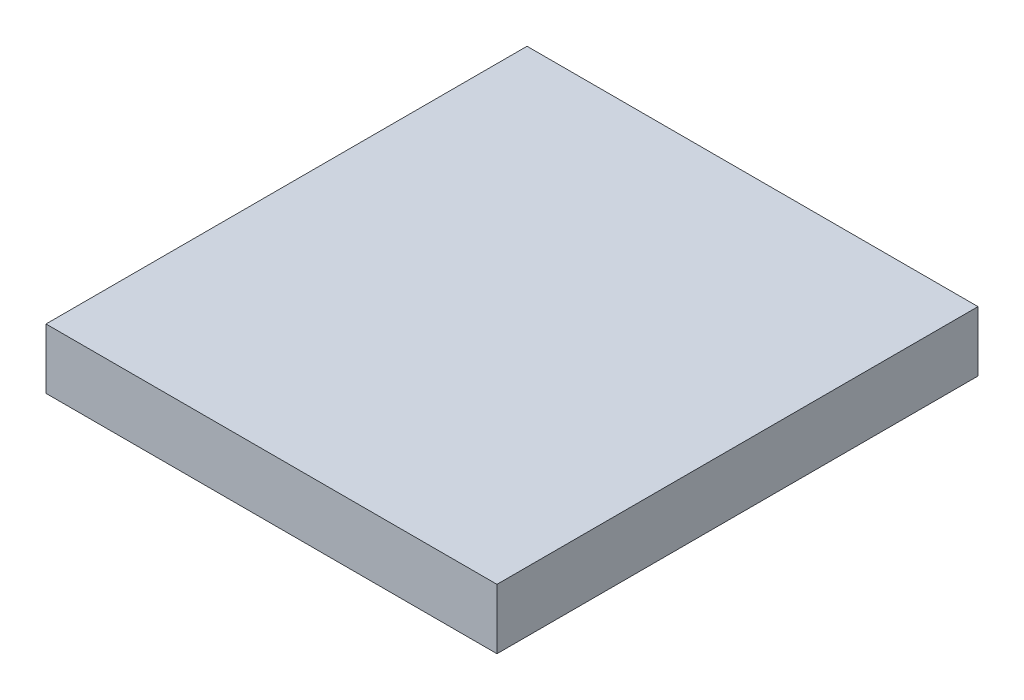
SolidWorks part; units mm, degrees
ref_plane "Front Plane" through (0, 0, 0) normal (0, 0, 1) x (1, 0, 0)
ref_plane "Top Plane" through (0, 0, 0) normal (0, 1, 0) x (1, 0, 0)
ref_plane "Right Plane" through (0, 0, 0) normal (1, 0, 0) x (0, 0, -1)
sketch "Sketch1" plane through (0, 0, 0) normal (0, 1, 0) x (1, 0, 0)
  line L0 (-74.7839, 129.2003) -> (-74.7839, -30.7997)
  line L1 (-74.7839, -30.7997) -> (75.2161, -30.7997)
  line L2 (75.2161, -30.7997) -> (75.2161, 129.2003)
  line L3 (75.2161, 129.2003) -> (-74.7839, 129.2003)
  dimension "D1" = 150
  dimension "D2" = 160
extrude "Boss-Extrude1" add sketch "Sketch1" along normal blind 20
sketch "Sketch2" plane through (0, 0, 0) normal (0, 1, 0) x (1, 0, 0)
  line L0 (-59.7839, 96.7003) -> (-59.7839, 29.2003)
  line L1 (-59.7839, 29.2003) -> (0.2161, 29.2003)
  line L2 (0.2161, 29.2003) -> (0.2161, 96.7003)
  line L3 (0.2161, 96.7003) -> (-59.7839, 96.7003)
  line L5 (-74.7839, -30.7997) -> (75.2161, -30.7997) construction
  line L7 (-74.7839, 129.2003) -> (-74.7839, -30.7997) construction
  line L8 (75.2161, 129.2003) -> (-74.7839, 129.2003) construction
  dimension "D1" = 67.5
  dimension "D2" = 60
  dimension "D3" = 15
  dimension "D4" = 60
  dimension "D5" = 32.5
extrude "Cut-Extrude1" cut sketch "Sketch2" against normal blind 15 and the other way blind 15
sketch "Sketch3" plane through (0, 0, 0) normal (0, 1, 0) x (1, 0, 0)
  line L0 (0.2161, 96.7003) -> (40.2161, 95.4503)
  line L1 (40.2161, 95.4503) -> (40.2161, 89.2003)
  line L2 (40.2161, 89.2003) -> (0.2161, 89.2003)
  line L3 (0.2161, 96.7003) -> (0.2161, 29.2003) construction
  line L4 (0.2161, 89.2003) -> (97.7865, 89.2003) construction
  line L5 (0.2161, 96.7003) -> (0.2161, 89.2003)
  dimension "D1" = 40
  dimension "D2" = 6.25
  dimension "D3" = 7.5
revolve "Cut-Revolve1" cut sketch "Sketch3" angle 360 about L4
sketch "Sketch4" plane through (0, 0, 0) normal (0, 1, 0) x (1, 0, 0)
  line L0 (0.2161, 79.2003) -> (60.2161, 77.9503)
  line L1 (0.2161, 81.7003) -> (0.2161, 29.2003) construction
  line L2 (60.2161, 77.9503) -> (60.2161, 71.7003)
  line L3 (60.2161, 71.7003) -> (0.2161, 71.7003)
  line L4 (0.2161, 71.7003) -> (0.2161, 79.2003)
  line L5 (94.9874, 71.7003) -> (-11.8608, 71.7003) construction
  dimension "D1" = 2.5
  dimension "D2" = 7.5
  dimension "D3" = 6.25
  dimension "D4" = 60
revolve "Cut-Revolve2" cut sketch "Sketch4" angle 360 about L5
sketch "Sketch6" plane through (0, 0, 0) normal (0, 1, 0) x (1, 0, 0)
  line L0 (0.2161, 61.7003) -> (60.2161, 60.4503)
  line L1 (0.2161, 64.2003) -> (0.2161, 29.2003) construction
  line L2 (60.2161, 60.4503) -> (60.2161, 54.2003)
  line L3 (60.2161, 54.2003) -> (0.2161, 54.2003)
  line L4 (0.2161, 54.2003) -> (0.2161, 61.7003)
  line L5 (60.2161, 54.2003) -> (0.2161, 54.2003) construction
  dimension "D1" = 60
  dimension "D2" = 6.25
  dimension "D3" = 7.5
  dimension "D4" = 2.5
revolve "Cut-Revolve3" cut sketch "Sketch6" angle 360 about L5
sketch "Sketch7" plane through (0, 0, 0) normal (0, 1, 0) x (1, 0, 0)
  line L0 (0.2161, 44.2003) -> (60.2161, 42.9503)
  line L1 (0.2161, 46.7003) -> (0.2161, 29.2003) construction
  line L2 (60.2161, 42.9503) -> (60.2161, 36.7003)
  line L3 (60.2161, 36.7003) -> (0.2161, 36.7003)
  line L4 (0.2161, 36.7003) -> (0.2161, 44.2003)
  line L5 (60.2161, 36.7003) -> (0.2161, 36.7003) construction
  dimension "D1" = 60
  dimension "D2" = 7.5
  dimension "D3" = 6.25
  dimension "D4" = 2.5
revolve "Cut-Revolve4" cut sketch "Sketch7" angle 360 about L5
sketch "Sketch11" plane through (0, 0, 0) normal (0, 1, 0) x (1, 0, 0)
  line L0 (-46.1439, 29.2003) -> (28.7625, 1.1104)
  line L1 (0.2161, 29.2003) -> (-59.7839, 29.2003) construction
  line L2 (28.7625, 1.1104) -> (31.3959, 8.1329)
  line L3 (31.3959, 8.1329) -> (-24.7839, 29.2003)
  line L4 (-24.7839, 29.2003) -> (-46.1439, 29.2003)
  line L5 (28.7625, 1.1104) -> (-46.1439, 29.2003) construction
  dimension "D1" = 7.5
  dimension "D2" = 80
  dimension "D3" = 13.64
  dimension "D4" = 25
  dimension "D5" = 60
revolve "Cut-Revolve5" cut sketch "Sketch11" angle 360 about L5
sketch "Sketch13" plane through (0, 0, 0) normal (0, 1, 0) x (1, 0, 0)
  line L0 (-30.0507, 15.1554) -> (-24.7839, 29.2003)
  line L1 (-24.7839, 29.2003) -> (-46.1439, 29.2003)
  line L2 (-46.1439, 29.2003) -> (-30.0507, 15.1554)
extrude "Cut-Extrude6" cut sketch "Sketch13" against normal blind 0.1 and the other way blind 10
sketch "Sketch15" plane through (0, 0, 0) normal (0, 1, 0) x (1, 0, 0)
  line L0 (60.2161, 36.7003) -> (-4.031, 36.7003) construction
  line L1 (60.2161, 30.4503) -> (60.2161, 42.9503) construction
  line L2 (50.2161, 30.242) -> (37.7161, 29.9815)
  line L3 (0.2161, 29.2003) -> (60.2161, 30.4503) construction
  line L6 (50.2161, 31.742) -> (50.2161, 30.242)
  line L7 (50.2161, 31.742) -> (37.7161, 31.4815)
  line L8 (37.7161, 31.4815) -> (37.7161, 29.9815)
  dimension "D1" = 10
  dimension "D2" = 12.5
  dimension "D3" = 1.5
revolve "Revolve2" add sketch "Sketch15" angle 180 about L0
sketch "Sketch16" plane through (0, 0, 0) normal (0, 1, 0) x (1, 0, 0)
  line L0 (60.2161, 36.7003) -> (-8.6318, 36.7003) construction
  line L1 (60.2161, 30.4503) -> (60.2161, 42.9503) construction
  line L2 (25.2161, 29.7211) -> (12.7161, 29.4607)
  line L3 (0.2161, 29.2003) -> (37.7161, 29.9815) construction
  line L6 (25.2161, 31.2211) -> (25.2161, 29.7211)
  line L8 (25.2161, 31.2211) -> (12.7161, 30.9607)
  line L9 (12.7161, 30.9607) -> (12.7161, 29.4607)
  line L10 (37.7161, 31.4815) -> (37.7161, 29.9815) construction
  dimension "D1" = 12.5
  dimension "D2" = 12.5
  dimension "D3" = 1.5
revolve "Revolve3" add sketch "Sketch16" angle 180 about L0
sketch "Sketch17" plane through (0, 0, 0) normal (0, 1, 0) x (1, 0, 0)
  line L0 (60.2161, 54.2003) -> (-2.2399, 54.2003) construction
  line L1 (60.2161, 47.9503) -> (60.2161, 60.4503) construction
  line L2 (50.2161, 47.742) -> (50.2161, 49.242)
  line L3 (0.2161, 46.7003) -> (60.2161, 47.9503) construction
  line L5 (37.7161, 48.9815) -> (37.7161, 47.4815)
  line L6 (37.7161, 47.4815) -> (50.2161, 47.742)
  line L7 (50.2161, 49.242) -> (37.7161, 48.9815)
  dimension "D1" = 1.5
  dimension "D2" = 1.5
  dimension "D3" = 12.5
  dimension "D4" = 10
revolve "Revolve4" add sketch "Sketch17" angle 180 about L0
sketch "Sketch18" plane through (0, 0, 0) normal (0, 1, 0) x (1, 0, 0)
  line L0 (60.2161, 54.2003) -> (-2.3771, 54.2003) construction
  line L1 (60.2161, 47.9503) -> (60.2161, 60.4503) construction
  line L2 (25.2161, 47.2211) -> (25.2161, 48.7211)
  line L3 (0.2161, 46.7003) -> (37.7161, 47.4815) construction
  line L4 (25.2161, 47.2211) -> (12.7161, 46.9607)
  line L5 (12.7161, 46.9607) -> (12.7161, 48.4607)
  line L6 (12.7161, 48.4607) -> (25.2161, 48.7211)
  line L7 (37.7161, 48.9815) -> (37.7161, 47.4815) construction
  dimension "D1" = 1.5
  dimension "D2" = 1.5
  dimension "D3" = 12.5
  dimension "D4" = 12.5
revolve "Revolve5" add sketch "Sketch18" angle 180 about L0
sketch "Sketch19" plane through (0, 0, 0) normal (0, 1, 0) x (1, 0, 0)
  line L0 (60.2161, 71.7003) -> (-2.6664, 71.7003) construction
  line L1 (60.2161, 65.4503) -> (60.2161, 77.9503) construction
  line L2 (50.2161, 65.242) -> (50.2161, 66.742)
  line L3 (0.2161, 64.2003) -> (60.2161, 65.4503) construction
  line L4 (50.2161, 65.242) -> (37.7161, 64.9815)
  line L5 (37.7161, 64.9815) -> (37.7161, 66.4815)
  line L6 (37.7161, 66.4815) -> (50.2161, 66.742)
  dimension "D1" = 10
  dimension "D2" = 12.5
  dimension "D3" = 1.5
  dimension "D4" = 1.5
revolve "Revolve6" add sketch "Sketch19" angle 180 about L0
sketch "Sketch20" plane through (0, 0, 0) normal (0, 1, 0) x (1, 0, 0)
  line L0 (60.2161, 71.7003) -> (-5.3603, 71.7003) construction
  line L1 (60.2161, 65.4503) -> (60.2161, 77.9503) construction
  line L2 (25.2161, 66.2211) -> (25.2161, 64.7211)
  line L3 (0.2161, 64.2003) -> (37.7161, 64.9815) construction
  line L4 (25.2161, 64.7211) -> (12.7161, 64.4607)
  line L5 (12.7161, 64.4607) -> (12.7161, 65.9607)
  line L6 (12.7161, 65.9607) -> (25.2161, 66.2211)
  line L7 (37.7161, 66.4815) -> (37.7161, 64.9815) construction
  dimension "D1" = 12.5
  dimension "D2" = 1.5
  dimension "D3" = 12.5
  dimension "D4" = 1.5
revolve "Revolve7" add sketch "Sketch20" angle 180 about L0
sketch "Sketch21" plane through (0, 0, 0) normal (0, 1, 0) x (1, 0, 0)
  line L0 (40.2161, 89.2003) -> (-5.481, 89.2003) construction
  line L1 (40.2161, 95.4503) -> (40.2161, 82.9503) construction
  line L2 (32.7161, 82.7159) -> (32.7161, 84.2159)
  line L3 (40.2161, 82.9503) -> (0.2161, 81.7003) construction
  line L4 (32.7161, 84.2159) -> (23.3411, 83.9229)
  line L5 (23.3411, 83.9229) -> (23.3411, 82.4229)
  line L6 (23.3411, 82.4229) -> (32.7161, 82.7159)
  dimension "D1" = 1.5
  dimension "D2" = 9.375
  dimension "D3" = 7.5
revolve "Revolve8" add sketch "Sketch21" angle 180 about L0
sketch "Sketch22" plane through (0, 0, 0) normal (0, 1, 0) x (1, 0, 0)
  line L0 (40.2161, 89.2003) -> (-5.8524, 89.2003) construction
  line L1 (40.2161, 95.4503) -> (40.2161, 82.9503) construction
  line L2 (13.9661, 82.13) -> (13.9661, 83.63)
  line L3 (23.3411, 82.4229) -> (0.2161, 81.7003) construction
  line L4 (13.9661, 83.63) -> (4.5911, 83.337)
  line L5 (4.5911, 83.337) -> (4.5911, 81.837)
  line L6 (4.5911, 81.837) -> (13.9661, 82.13)
  line L7 (23.3411, 83.9229) -> (23.3411, 82.4229) construction
  dimension "D1" = 1.5
  dimension "D2" = 9.375
  dimension "D3" = 9.375
  dimension "D4" = 1.5
revolve "Revolve9" add sketch "Sketch22" angle 180 about L0
sketch "Sketch23" plane through (0, 0, 0) normal (0, 1, 0) x (1, 0, 0)
  line L0 (28.7625, 1.1104) -> (-32.6001, 24.1214) construction
  line L1 (26.129, -5.9121) -> (31.3959, 8.1329) construction
  line L2 (17.2924, -0.9963) -> (16.7657, -2.4008)
  line L3 (-30.0507, 15.1554) -> (26.129, -5.9121) construction
  line L4 (16.7657, -2.4008) -> (5.0616, 1.9882)
  line L5 (5.0616, 1.9882) -> (5.5883, 3.3927)
  line L6 (5.5883, 3.3927) -> (17.2924, -0.9963)
  dimension "D1" = 10
  dimension "D2" = 1.5
  dimension "D3" = 1.5
  dimension "D4" = 12.5
revolve "Revolve10" add sketch "Sketch23" angle 180 about L0
sketch "Sketch25" plane through (0, 0, 0) normal (0, 1, 0) x (1, 0, 0)
  line L0 (28.7625, 1.1104) -> (-30.6583, 23.3932) construction
  line L1 (26.129, -5.9121) -> (31.3959, 8.1329) construction
  line L7 (-6.1158, 7.7818) -> (-6.6425, 6.3773)
  line L8 (-30.0507, 15.1554) -> (5.0616, 1.9882) construction
  line L9 (-6.6425, 6.3773) -> (-18.3466, 10.7663)
  line L10 (-18.3466, 10.7663) -> (-17.8199, 12.1708)
  line L11 (-17.8199, 12.1708) -> (-6.1158, 7.7818)
  line L12 (5.5883, 3.3927) -> (5.0616, 1.9882) construction
  dimension "D1" = 12.5
  dimension "D2" = 1.5
  dimension "D3" = 1.5
  dimension "D4" = 12.5
revolve "Revolve11" add sketch "Sketch25" angle 180 about L0
